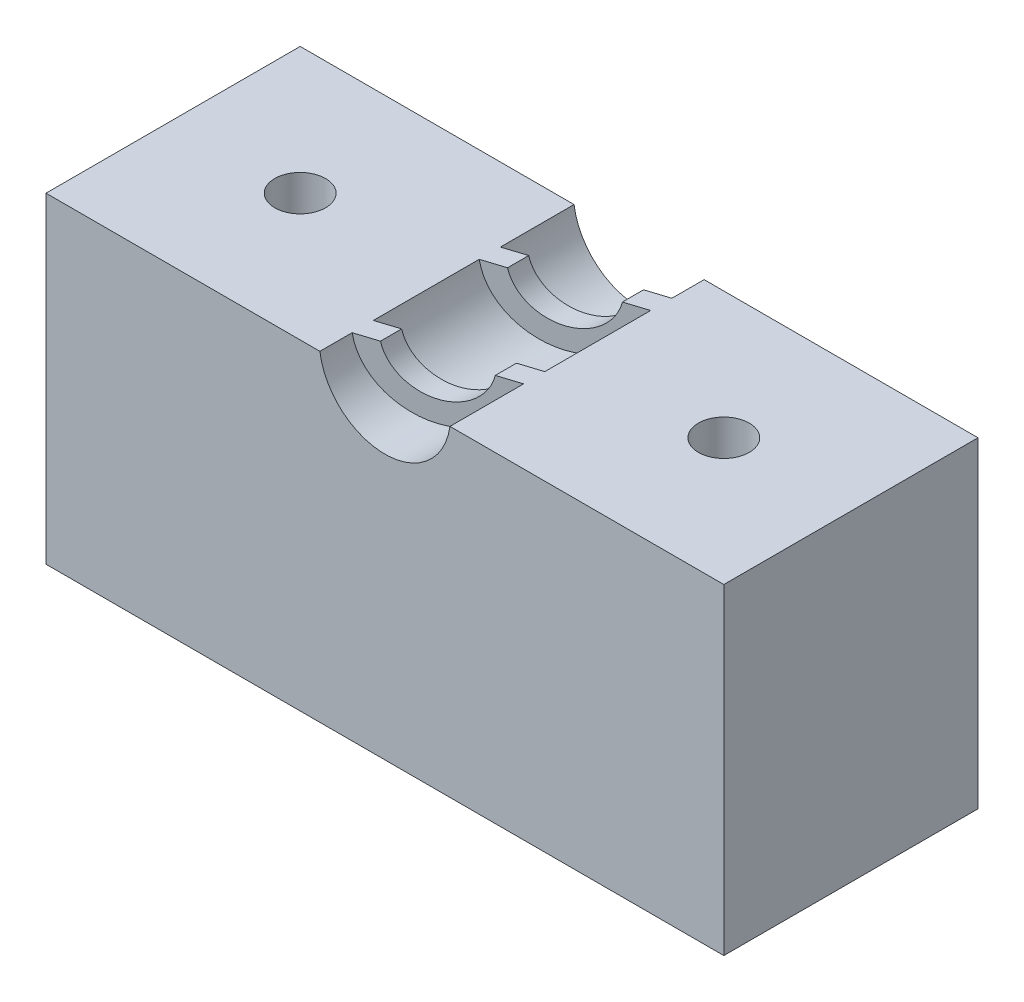
SolidWorks part; units mm, degrees
ref_plane "前视基准面" through (0, 0, 0) normal (0, 0, 1) x (1, 0, 0)
ref_plane "上视基准面" through (0, 0, 0) normal (0, 1, 0) x (1, 0, 0)
ref_plane "右视基准面" through (0, 0, 0) normal (1, 0, 0) x (0, 0, -1)
other "Configuration Table"
sketch "草图1" plane through (0, 0, 0) normal (0, 0, 1) x (1, 0, 0)
  line L1 (-8, -8) -> (8, -8)
  line L2 (-8, -8) -> (-8, 8)
  line L3 (-8, 8) -> (8, 8)
  line L4 (8, -8) -> (8, 8)
  line L5 (-8, -8) -> (8, 8) construction
  line L6 (-8, 8) -> (8, -8) construction
  circle A0 centre (0, 0) radius 1.55
  point P0 (0, 0)
  dimension "D3" = 3.1
  dimension "D1" = 16
  dimension "D2" = 16
extrude "凸台-拉伸1" add sketch "草图1" along normal mid plane 6
sketch "草图6" plane through (0, 0, 0) normal (0, 1, 0) x (1, 0, 0)
  line L0 (-1.55, -3) -> (1.55, -3) construction
  line L1 (1.55, 3) -> (-1.55, 3) construction
  line L2 (-1.55, -3) -> (1.55, -3)
  line L3 (1.55, 3) -> (-1.55, 3)
  line L4 (-1.55, 3) -> (-1.55, -3)
  line L5 (1.55, -3) -> (1.55, 3)
  line L6 (-1.55, 0.7565) -> (1.55, 1.7435)
  line L7 (1.55, 1.7435) -> (1.55, 2.2435)
  line L8 (1.55, 2.2435) -> (-1.55, 1.2565)
  line L9 (-1.55, -1.7435) -> (1.55, -0.7565)
  line L10 (-1.55, -2.2435) -> (1.55, -1.2565)
  line L11 (-2.0945, -0.6668) -> (3.135, 0.9981) construction
  line L12 (-3.1004, 0) -> (4.2723, 0) construction
  dimension "D1" = 2.5
  dimension "D2" = 0.5
  dimension "D3" = 0.5
  dimension "D4" = 17.66
extrude "凸台-拉伸2" add sketch "草图6" against normal up to surface (8 mm away) contours L4 L10 L5 L9 | L5 L8 L4 L6 up to face at (0, -8, 0)
sketch "草图7" plane through (0, 0, 0) normal (0, 0, 1) x (1, 0, 0)
  line L0 (0, 0) -> (-1.0279, -0.2141)
  line L1 (0, 0) -> (1.0279, -0.2141)
  line L2 (-1.0279, -0.2141) -> (-8, -0.2141)
  line L3 (1.0279, -0.2141) -> (8, -0.2141)
  line L6 (8, -8) -> (8, 8)
  line L7 (-8, -8) -> (8, -8)
  line L8 (-8, 8) -> (-8, -8)
  line L9 (8, 8) -> (-8, 8)
  line L10 (8, -8) -> (8, 8)
  line L11 (-8, -8) -> (8, -8)
  line L12 (-8, 8) -> (-8, -8)
  line L13 (8, 8) -> (-8, 8)
  circle A0 centre (0, 0) radius 1.05
  dimension "D1" = 2.1
  dimension "D2" = 0
  dimension "D3" = 156.47
extrude "切除-拉伸2" cut sketch "草图7" against normal through all both and the other way through all contours A0 L3 L10 L13 L12 L2 | L1 A0 L0 | L0 A0 L1
sketch "草图8" plane through (0, 0, 0) normal (0, 1, 0) x (1, 0, 0)
  line L0 (0, 5.5834) -> (0, -5.0797) construction
  circle A0 centre (-5, 0) radius 0.6
  circle A1 centre (5, 0) radius 0.6
  dimension "D2" = 1.2
  dimension "D3" = 10
extrude "切除-拉伸3" cut sketch "草图8" against normal through all
sketch "草图10" plane through (0, -8, 0) normal (0, -1, 0) x (1, 0, 0)
  line L4 (-8, -3) -> (8, -3)
  line L5 (8, -3) -> (8, 3)
  line L6 (8, 3) -> (-8, 3)
  line L7 (-8, 3) -> (-8, -3)
  line L8 (-8, -3) -> (8, -3)
  line L9 (8, -3) -> (8, 3)
  line L10 (8, 3) -> (-8, 3)
  line L11 (-8, 3) -> (-8, -3)
  circle A0 centre (-5, 0) radius 0.6 construction
  circle A1 centre (5, 0) radius 0.6 construction
  circle A2 centre (-5, 0) radius 0.6
  circle A3 centre (5, 0) radius 0.6
  dimension "D1" = 0
extrude "切除-拉伸7" cut sketch "草图10" against normal blind 0.2
equation "\"x\"=0.8094"
